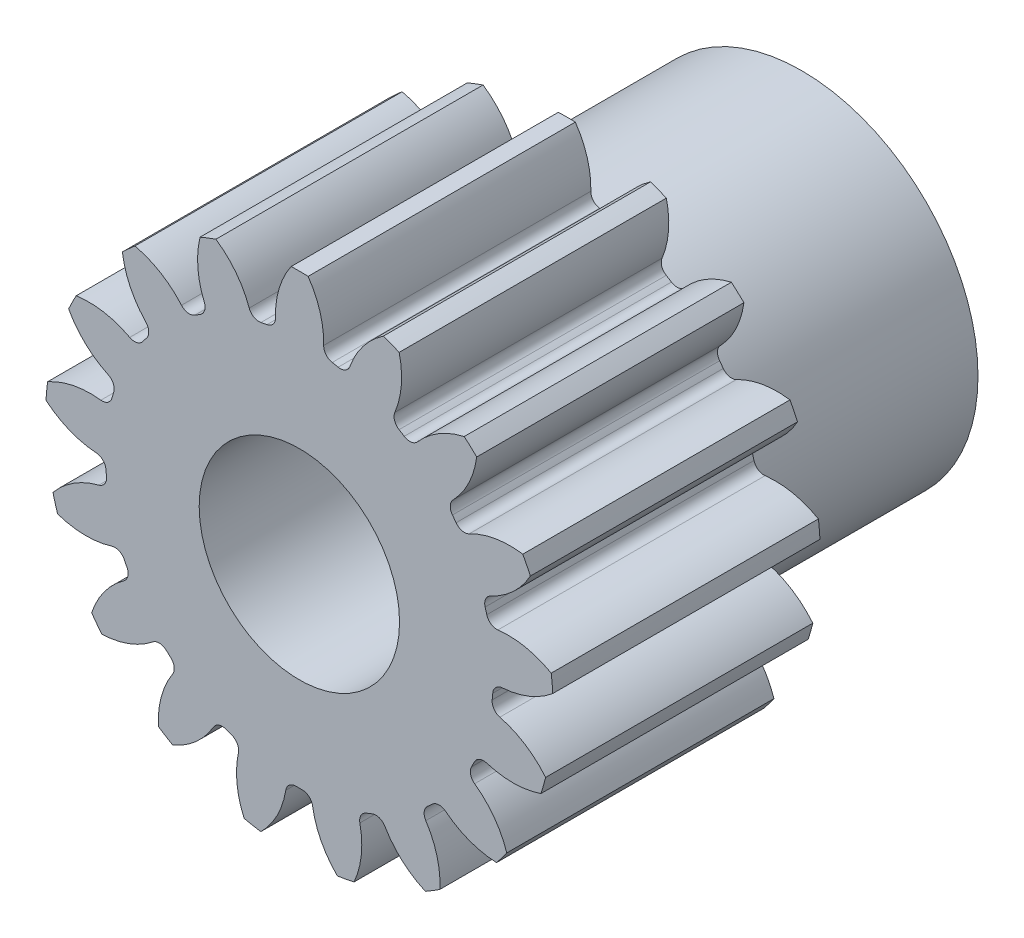
SolidWorks part; units mm, degrees
ref_plane "Front" through (0, 0, 0) normal (0, 0, 1) x (1, 0, 0)
ref_plane "Top" through (0, 0, 0) normal (0, 1, 0) x (1, 0, 0)
ref_plane "Right" through (0, 0, 0) normal (1, 0, 0) x (0, 0, -1)
sketch "Sketch3" plane through (0, 0, 0) normal (0, 0, 1) x (1, 0, 0)
  circle A0 centre (0, 0) radius 12.065
  dimension "od" = 24.13
extrude "gearBody" add sketch "Sketch3" along normal blind 12.7
sketch "Sketch2" plane through (0, 0, 0) normal (0, 0, 1) x (1, 0, 0)
  line L0 (0, 0) -> (9.3718, 3.8819) construction
  line L1 (12.2971, -3.893) -> (0, 0) construction
  line L2 (0, 0) -> (36.3143, 0) construction
  line L3 (10.795, -0.0244) -> (10.6114, -1.9827) construction
  line L5 (10.7032, -1.0035) -> (0, 0) construction
  line L7 (0, 0) -> (10.144, 0) construction
  arc A0 (10.1419, -0.2036) -> (10.003, -1.6852) centre (0, 0) ccw construction
  arc A1 (12.0448, 0.6977) -> (11.7052, -2.9245) centre (0, 0) ccw construction
  arc A2 (10.795, -0.0244) -> (10.6114, -1.9827) centre (0, 0) ccw construction
  arc A3 (9.1653, -1.0044) -> (9.1923, -0.7168) centre (0, 0) ccw
  arc A4 (12.2971, -3.893) -> (9.5292, -1.5317) centre (8.4869, -5.5564) ccw
  arc A5 (12.2971, -3.893) -> (12.8064, 1.5393) centre (0, 0) ccw
  arc A6 (12.8064, 1.5393) -> (9.6479, -0.2664) centre (9.3718, 3.8819) cw
  arc A7 (9.1923, -0.7168) -> (9.6479, -0.2664) centre (9.6804, -0.7549) cw
  arc A8 (9.5292, -1.5317) -> (9.1653, -1.0044) centre (9.652, -1.0578) cw
  point P6 (12.8064, 1.5393)
  point P22 (12.2971, -3.893)
  dimension "baseDia" = 20.288
  dimension "od" = 24.13
  dimension "pd" = 21.59
  dimension "rd" = 18.4404
  dimension "rFillet" = 0.4896
  dimension "pointX" = 12.8064
  dimension "pointY" = 1.5393
  dimension "CTT" = 1.9583
  dimension "flankCenterAngle" = 22.5
extrude "toothCut" cut sketch "Sketch2" along normal through all
pattern_circular "CirPattern1" count 17 over 360 about axis through (0, 0, 0) along (0, 0, 1) of "toothCut"
sketch "hub1Dia" plane through (0, 0, 0) normal (0, 0, -1) x (-1, 0, 0)
  circle A0 centre (0, 0) radius 8.382
  dimension "hub1Dia" = 16.764
extrude "hub1" add sketch "hub1Dia" along normal blind 11.176
sketch "hub2Dia" plane through (0, 0, 12.7) normal (0, 0, 1) x (1, 0, 0)
  circle A0 centre (0, 0) radius 12.7
  dimension "hub2dia" = 25.4
sketch "boreDia" plane through (0, 0, 0) normal (0, 0, 1) x (1, 0, 0)
  circle A0 centre (0, 0) radius 4.7625
  dimension "boreDia" = 9.525
extrude "bore" cut sketch "boreDia" against normal mid plane 25400
